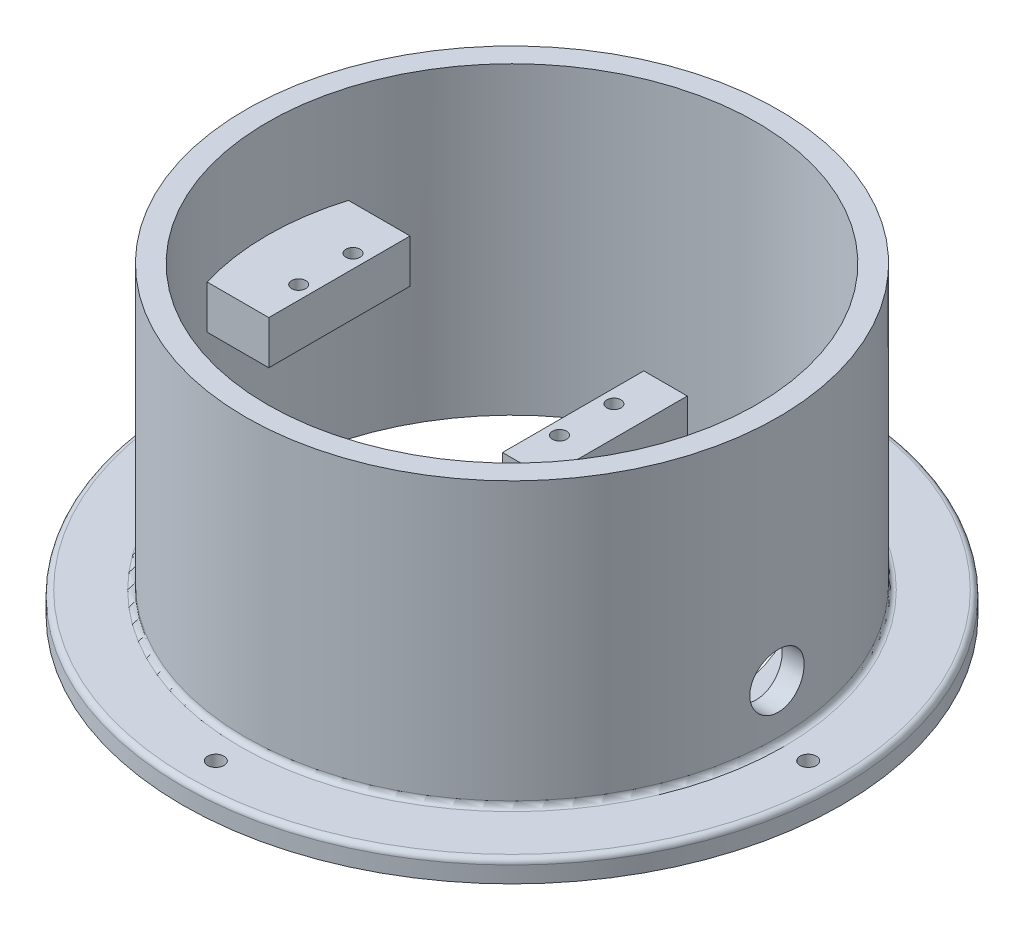
SolidWorks part; units mm, degrees
ref_plane "Front Plane" through (0, 0, 0) normal (0, 0, 1) x (1, 0, 0)
ref_plane "Top Plane" through (0, 0, 0) normal (0, 1, 0) x (1, 0, 0)
ref_plane "Right Plane" through (0, 0, 0) normal (1, 0, 0) x (0, 0, -1)
sketch "Sketch1" plane through (0, 0, 0) normal (0, 1, 0) x (1, 0, 0)
  circle A0 centre (0, 0) radius 45
  circle A1 centre (0, 0) radius 60.625
  dimension "D1" = 90
  dimension "D2" = 121.25
extrude "Boss-Extrude1" add sketch "Sketch1" along normal blind 4
sketch "Sketch2" plane through (0, 4, 0) normal (0, 1, 0) x (1, 0, 0)
  circle A0 centre (0, 0) radius 49
  circle A1 centre (0, 0) radius 45
  dimension "D1" = 90
  dimension "D2" = 98
extrude "Boss-Extrude2" add sketch "Sketch2" along normal blind 52
sketch "Sketch3" plane through (0, 0, 0) normal (0, 0, 1) x (1, 0, 0)
  line L0 (-60.625, 0) -> (60.625, 0) construction
  line L1 (11.25, 0) -> (19.25, 0)
  line L2 (11.25, 0) -> (11.25, 38)
  line L3 (11.25, 38) -> (19.25, 38)
  line L4 (19.25, 0) -> (19.25, 38)
  line L5 (49, 56) -> (-49, 56) construction
  line L6 (-46.75, 38) -> (-31.75, 38)
  line L7 (-46.75, 38) -> (-46.75, 30)
  line L8 (-46.75, 30) -> (-31.75, 30)
  line L9 (-31.75, 38) -> (-31.75, 30)
  dimension "D1" = 8
  dimension "D2" = 11.25
  dimension "D3" = 38
  dimension "D4" = 43
  dimension "D5" = 15
  dimension "D6" = 8
  dimension "D7" = 18
extrude "Boss-Extrude3" add sketch "Sketch3" along normal mid plane 26
sketch "Sketch4" plane through (11.25, 0, 0) normal (-1, 0, 0) x (0, 0, 1)
  line L0 (0, 0) -> (0, 56) construction
  line L1 (49, 56) -> (-49, 56) construction
  line L2 (-60.625, 0) -> (60.625, 0) construction
  line L3 (-5, 5) -> (5, 5)
  line L4 (-5, 5) -> (-5, 29)
  line L5 (-5, 29) -> (5, 29)
  line L6 (5, 5) -> (5, 29)
  line L7 (-5, 5) -> (5, 29) construction
  line L8 (-5, 29) -> (5, 5) construction
  point P5 (0, 17)
  dimension "D1" = 5
  dimension "D2" = 24
  dimension "D3" = 10
extrude "Cut-Extrude1" cut sketch "Sketch4" against normal up to next (8 mm away)
sketch "Sketch5" plane through (11.25, 0, 0) normal (-1, 0, 0) x (0, 0, 1)
  line L0 (0, 0) -> (0, 56) construction
  line L1 (49, 56) -> (-49, 56) construction
  circle A0 centre (0, 14) radius 5
  dimension "D2" = 10
  dimension "D1" = 14
extrude "Cut-Extrude2" cut sketch "Sketch5" against normal through all
sketch "Sketch6" plane through (0, 38, 0) normal (0, 1, 0) x (1, 0, 0)
  line L0 (0, 0) -> (-45, 0) construction
  line L1 (-45, 0) -> (45, 0) construction
  line L2 (-31.75, -13) -> (-31.75, 13) construction
  line L3 (-34.25, 5) -> (13.75, 5) construction
  line L4 (-34.25, 5) -> (-34.25, -5) construction
  line L5 (-34.25, -5) -> (13.75, -5) construction
  line L6 (13.75, 5) -> (13.75, -5) construction
  line L7 (11.25, -13) -> (11.25, 13) construction
  arc A0 (-43.0813, 13) -> (-43.0813, -13) centre (0, 0) ccw construction
  circle A1 centre (0, 0) radius 45 construction
  circle A2 centre (-34.25, 5) radius 1.3
  circle A3 centre (-34.25, -5) radius 1.3
  circle A4 centre (13.75, 5) radius 1.3
  circle A5 centre (13.75, -5) radius 1.3
  dimension "D5" = 2.6
  dimension "D1" = 5
  dimension "D2" = 5
  dimension "D3" = 2.5
  dimension "D4" = 2.5
extrude "Cut-Extrude3" cut sketch "Sketch6" against normal blind 7.2
sketch "Sketch7" plane through (0, 0, 0) normal (0, -1, 0) x (1, 0, 0)
  line L0 (11.25, 13) -> (25.2498, 37.2484)
  line L1 (19.25, 0) -> (80.9948, 0) construction
  line L2 (19.25, 13) -> (19.25, -13) construction
  line L3 (11.25, -13) -> (25.2498, -37.2484)
  line L4 (11.25, 13) -> (11.25, -13)
  line L5 (24.25, 19.5167) -> (27.3618, 24.9065)
  line L6 (24.25, -19.5167) -> (27.3618, -24.9065)
  line L8 (24.25, 19.5167) -> (24.25, -19.5167)
  line L10 (19.25, 10.8564) -> (19.25, -10.8564) construction
  line L11 (19.25, 10.8564) -> (27.3618, 24.9065) construction
  line L12 (19.25, -10.8564) -> (27.3618, -24.9065) construction
  circle A0 centre (0, 0) radius 45 construction
  arc A1 (25.2498, -37.2484) -> (25.2498, 37.2484) centre (0, 0) ccw
  arc A2 (27.3618, -24.9065) -> (27.3618, 24.9065) centre (0, 0) ccw
  dimension "D1" = 60
  dimension "D3" = 5
  dimension "D2" = 8
extrude "Boss-Extrude4" add sketch "Sketch7" against normal blind 4
sketch "Sketch8" plane through (0, 0, 0) normal (0, -1, 0) x (1, 0, 0)
  circle A0 centre (0, 0) radius 54.5 construction
  circle A1 centre (54.5, 0) radius 1.5
  circle A2 centre (0, -54.5) radius 1.5
  circle A3 centre (-54.5, 0) radius 1.5
  circle A4 centre (0, 54.5) radius 1.5
  point P14 (0, 0)
  dimension "D1" = 109
  dimension "D2" = 3
  dimension "D3" = 4
extrude "Cut-Extrude4" cut sketch "Sketch8" against normal through all
fillet "Fillet1" radius 1 1 edges at (0, 4, 49)
fillet "Fillet2" radius 1 1 edges at (0, 4, 60.625)
